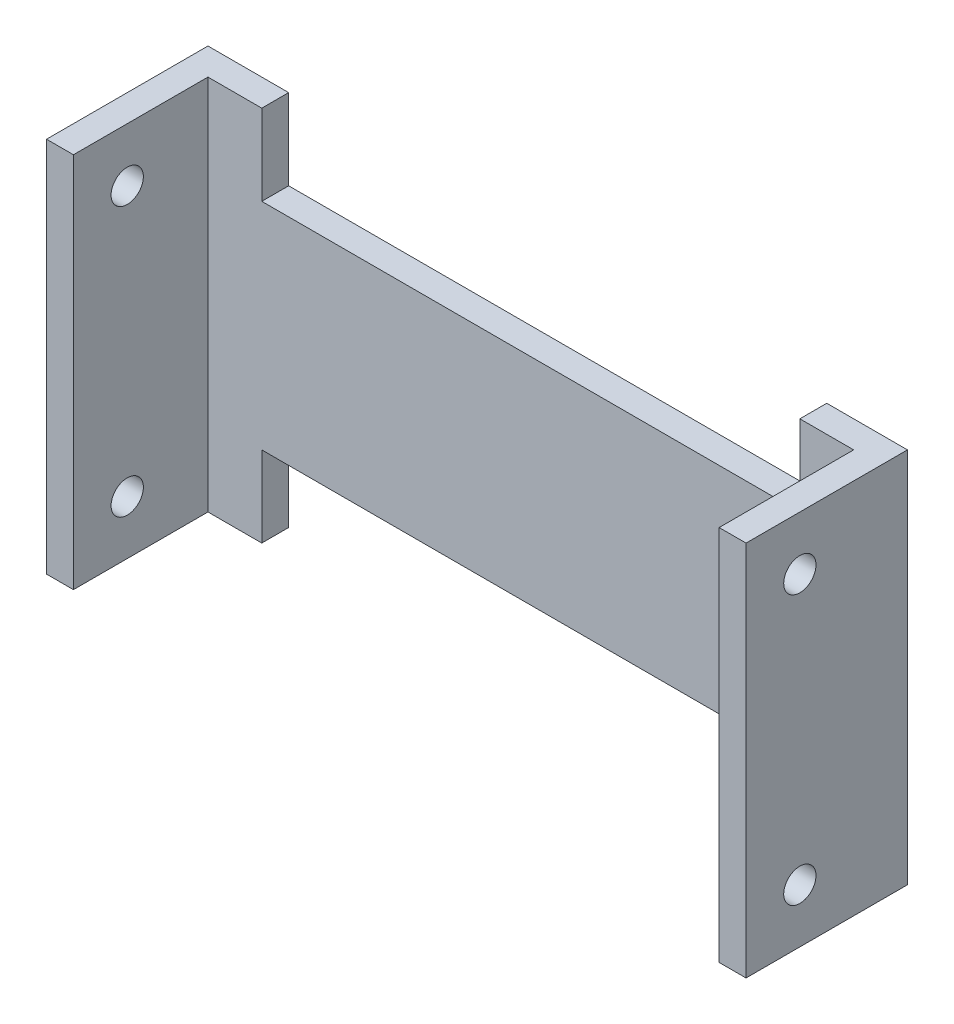
SolidWorks part; units mm, degrees
ref_plane "Front Plane" through (0, 0, 0) normal (0, 0, 1) x (1, 0, 0)
ref_plane "Top Plane" through (0, 0, 0) normal (0, 1, 0) x (1, 0, 0)
ref_plane "Right Plane" through (0, 0, 0) normal (1, 0, 0) x (0, 0, -1)
sketch "Sketch1" plane through (0, 0, 0) normal (0, 1, 0) x (1, 0, 0)
  line L0 (0, 0) -> (65, 0)
  line L5 (65, 0) -> (65, -30)
  line L6 (0, -5) -> (60, -5)
  line L7 (60, -5) -> (60, -30)
  line L8 (60, -30) -> (65, -30)
  line L9 (0, 23.6596) -> (0, -42.9239) construction
  line L10 (0, 0) -> (-65, 0)
  line L11 (-65, 0) -> (-65, -30)
  line L12 (-60, -30) -> (-65, -30)
  line L13 (-60, -5) -> (-60, -30)
  line L14 (0, -5) -> (-60, -5)
  dimension "D1" = 65
  dimension "D2" = 30
  dimension "D3" = 5
extrude "Boss-Extrude1" add sketch "Sketch1" along normal mid plane 70
sketch "Sketch2" plane through (0, 0, 0) normal (0, 0, -1) x (-1, 0, 0)
  line L0 (-50, -35) -> (-50, -20)
  line L1 (-65, -35) -> (65, -35) construction
  line L2 (-50, -20) -> (50, -20)
  line L3 (50, -20) -> (50, -35)
  line L4 (0, 0) -> (0, -20) construction
  line L5 (-65, 0) -> (65, 0) construction
  line L6 (-65, 35) -> (-65, -35) construction
  line L7 (65, 35) -> (65, -35) construction
  line L8 (50, 20) -> (50, 35)
  line L9 (-50, 35) -> (-50, 20)
  line L10 (-50, 20) -> (50, 20)
  line L11 (-50, 35) -> (50, 35)
  line L12 (-50, -35) -> (50, -35)
  dimension "D1" = 100
  dimension "D2" = 15
extrude "Cut-Extrude1" cut sketch "Sketch2" against normal up to surface (5 mm away) up to face at (0, 0, 5)
sketch "Sketch3" plane through (-65, 0, 0) normal (-1, 0, 0) x (0, 0, 1)
  line L0 (0, 0) -> (30, 0) construction
  line L1 (30, 35) -> (30, -35) construction
  circle A0 centre (20, 25) radius 3
  circle A2 centre (20, -25) radius 3
  dimension "D2" = 6
  dimension "D1" = 25
  dimension "D3" = 20
extrude "Cut-Extrude2" cut sketch "Sketch3" against normal through all
sketch "Sketch4" plane through (0, 0, 0) normal (0, 0, -1) x (-1, 0, 0)
  circle A0 centre (0, 0) radius 8
  dimension "D1" = 16
extrude "Cut-Extrude3" cut sketch "Sketch4" against normal blind 3
